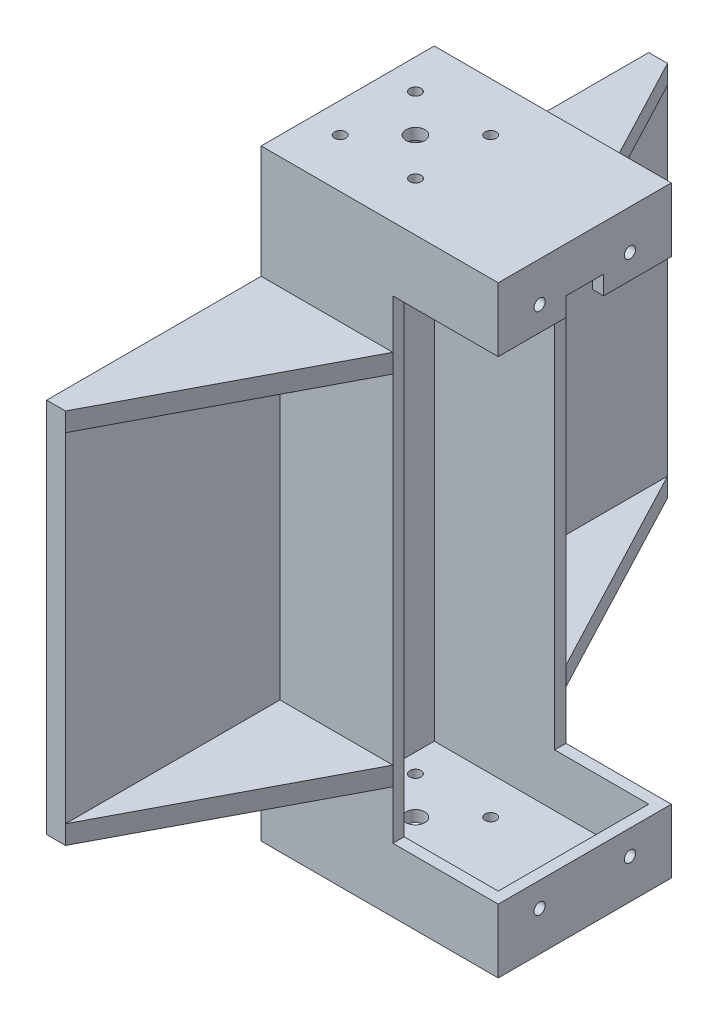
SolidWorks part; units mm, degrees
ref_plane "前视基准面" through (0, 0, 0) normal (0, 0, 1) x (1, 0, 0)
ref_plane "上视基准面" through (0, 0, 0) normal (0, 1, 0) x (1, 0, 0)
ref_plane "右视基准面" through (0, 0, 0) normal (1, 0, 0) x (0, 0, -1)
sketch "Sketch1" plane through (0, 0, 0) normal (0, 1, 0) x (1, 0, 0)
  line L1 (-30, 20) -> (30, 20)
  line L2 (-30, 20) -> (-30, -20)
  line L3 (-30, -20) -> (30, -20)
  line L4 (30, 20) -> (30, -20)
  line L5 (-30, 20) -> (30, -20) construction
  line L6 (-30, -20) -> (30, 20) construction
  point P0 (0, 0)
extrude "Extrude1" add sketch "Sketch1" along normal blind 3
sketch "Sketch2" plane through (0, 3, 0) normal (0, 1, 0) x (1, 0, 0)
  line L0 (-30, -20) -> (30, -20) construction
  line L1 (30, 20) -> (27, 20)
  line L2 (30, 20) -> (30, -20)
  line L3 (30, -20) -> (27, -20)
  line L4 (27, 20) -> (27, -20)
extrude "Extrude2" add sketch "Sketch2" along normal blind 14
sketch "Sketch4" plane through (27, 0, 0) normal (-1, 0, 0) x (0, 0, 1)
  circle A1 centre (-12, 10.5) radius 1.5
  circle A2 centre (12, 10.5) radius 1.5
extrude "Extrude3" cut sketch "Sketch4" against normal blind 15
sketch "Sketch5" plane through (0, 0, -20) normal (0, 0, -1) x (-1, 0, 0)
  line L1 (30, 3) -> (-27, 3)
  line L2 (-27, 3) -> (-27, 17)
  line L3 (-27, 17) -> (30, 17)
  line L4 (30, 17) -> (30, 3)
extrude "Extrude4" add sketch "Sketch5" against normal blind 3
sketch "Sketch6" plane through (0, 0, 20) normal (0, 0, 1) x (1, 0, 0)
  line L4 (27, 17) -> (-30, 17)
  line L5 (-30, 17) -> (-30, 3)
  line L6 (-30, 3) -> (27, 3)
  line L7 (27, 3) -> (27, 17)
  line L8 (27, 17) -> (-30, 17)
  line L9 (-30, 17) -> (-30, 3)
  line L10 (-30, 3) -> (27, 3)
  line L11 (27, 3) -> (27, 17)
  dimension "D1" = 0
extrude "Extrude5" add sketch "Sketch6" against normal blind 3
sketch "Sketch7" plane through (0, 3, 0) normal (0, 1, 0) x (1, 0, 0)
  circle A0 centre (-5, 10) radius 1.5
  circle A1 centre (-25, 10) radius 1.5
  circle A2 centre (-25, -10) radius 1.5
  circle A3 centre (-5, -10) radius 1.5
extrude "Extrude6" cut sketch "Sketch7" against normal blind 3
sketch "Sketch8" plane through (0, 3, 0) normal (0, 1, 0) x (1, 0, 0)
  circle A0 centre (-15, 0) radius 2.5
extrude "Extrude7" cut sketch "Sketch8" against normal blind 3
sketch "Sketch9" plane through (-30, 0, 0) normal (-1, 0, 0) x (0, 0, 1)
  line L1 (-20, 17) -> (20, 17)
  line L2 (-20, 17) -> (-20, 0)
  line L3 (-20, 0) -> (20, 0)
  line L4 (20, 17) -> (20, 0)
extrude "Extrude8" add sketch "Sketch9" along normal blind 3
sketch "Sketch10" plane through (0, 17, 0) normal (0, 1, 0) x (1, 0, 0)
  line L0 (-30, -17) -> (-30, 17) construction
  line L1 (-30, -17) -> (-30, 17)
  line L2 (-30, 17) -> (27, 17) construction
  line L3 (-30, 17) -> (2, 17)
  line L4 (-33, 20) -> (-33, -20)
  line L5 (-33, -20) -> (30, -20)
  line L6 (30, -20) -> (30, 20)
  line L7 (30, 20) -> (-33, 20)
  line L8 (-33, 20) -> (-33, -20)
  line L9 (-33, -20) -> (2, -20)
  line L11 (2, 20) -> (-33, 20)
  line L12 (27, -17) -> (-30, -17) construction
  line L13 (2, -17) -> (-30, -17)
  line L14 (2, 20) -> (2, 17)
  line L15 (2, -17) -> (2, -20)
  dimension "D1" = 0
extrude "Extrude9" add sketch "Sketch10" along normal blind 63
mirror "Mirror2" about plane through (0, 80, 0) normal (0, 1, 0) of bodies 114
sketch "Sketch11" plane through (0, 0, 20) normal (0, 0, 1) x (1, 0, 0)
  line L8 (-33, 0) -> (30, 0)
  line L9 (30, 0) -> (30, 17)
  line L10 (30, 17) -> (2, 17)
  line L11 (2, 17) -> (2, 143)
  line L12 (2, 143) -> (30, 143)
  line L13 (30, 143) -> (30, 160)
  line L14 (30, 160) -> (-33, 160)
  line L15 (-33, 160) -> (-33, 0)
  line L16 (-33, 0) -> (30, 0)
  line L17 (30, 0) -> (30, 17)
  line L18 (30, 17) -> (2, 17)
  line L19 (2, 17) -> (2, 143)
  line L20 (2, 143) -> (30, 143)
  line L21 (30, 143) -> (30, 160)
  line L22 (30, 160) -> (-33, 160)
  line L23 (-33, 160) -> (-33, 0)
  dimension "D1" = 0
extrude "Extrude10" add sketch "Sketch11" along normal blind 3
sketch "Sketch12" plane through (0, 0, -20) normal (0, 0, -1) x (-1, 0, 0)
  line L8 (-30, 0) -> (33, 0)
  line L9 (33, 0) -> (33, 160)
  line L10 (33, 160) -> (-30, 160)
  line L11 (-30, 160) -> (-30, 143)
  line L12 (-30, 143) -> (-2, 143)
  line L13 (-2, 143) -> (-2, 17)
  line L14 (-2, 17) -> (-30, 17)
  line L15 (-30, 17) -> (-30, 0)
  line L16 (-30, 0) -> (33, 0)
  line L17 (33, 0) -> (33, 160)
  line L18 (33, 160) -> (-30, 160)
  line L19 (-30, 160) -> (-30, 143)
  line L20 (-30, 143) -> (-2, 143)
  line L21 (-2, 143) -> (-2, 17)
  line L22 (-2, 17) -> (-30, 17)
  line L23 (-30, 17) -> (-30, 0)
  dimension "D1" = 0
extrude "Extrude11" add sketch "Sketch12" along normal blind 3
sketch "Sketch13" plane through (0, 0, 17) normal (0, 0, -1) x (-1, 0, 0)
  line L8 (-27, 17) -> (-27, 3)
  line L9 (-27, 3) -> (30, 3)
  line L10 (30, 3) -> (30, 157)
  line L11 (30, 157) -> (-27, 157)
  line L12 (-27, 157) -> (-27, 143)
  line L13 (-27, 143) -> (-2, 143)
  line L14 (-2, 143) -> (-2, 17)
  line L15 (-2, 17) -> (-27, 17)
  line L16 (-27, 17) -> (-27, 3)
  line L17 (-27, 3) -> (30, 3)
  line L18 (30, 3) -> (30, 157)
  line L19 (30, 157) -> (-27, 157)
  line L20 (-27, 157) -> (-27, 143)
  line L21 (-27, 143) -> (-2, 143)
  line L22 (-2, 143) -> (-2, 17)
  line L23 (-2, 17) -> (-27, 17)
  dimension "D1" = 0
extrude "Extrude12" cut sketch "Sketch13" against normal blind 3
sketch "Sketch14" plane through (0, 0, -17) normal (0, 0, 1) x (1, 0, 0)
  line L8 (27, 17) -> (2, 17)
  line L9 (2, 17) -> (2, 143)
  line L10 (2, 143) -> (27, 143)
  line L11 (27, 143) -> (27, 157)
  line L12 (27, 157) -> (-30, 157)
  line L13 (-30, 157) -> (-30, 3)
  line L14 (-30, 3) -> (27, 3)
  line L15 (27, 3) -> (27, 17)
  line L16 (27, 17) -> (2, 17)
  line L17 (2, 17) -> (2, 143)
  line L18 (2, 143) -> (27, 143)
  line L19 (27, 143) -> (27, 157)
  line L20 (27, 157) -> (-30, 157)
  line L21 (-30, 157) -> (-30, 3)
  line L22 (-30, 3) -> (27, 3)
  line L23 (27, 3) -> (27, 17)
  dimension "D1" = 0
extrude "Extrude13" cut sketch "Sketch14" against normal blind 3
sketch "Sketch15" plane through (-33, 0, 0) normal (-1, 0, 0) x (0, 0, 1)
  line L4 (80, 130) -> (-80, 130)
  line L5 (80, 130) -> (80, 30)
  line L6 (80, 30) -> (-80, 30)
  line L7 (-80, 130) -> (-80, 30)
  line L8 (80, 130) -> (-80, 30) construction
  line L9 (80, 30) -> (-80, 130) construction
  point P0 (0, 0)
  point P6 (0, 80)
extrude "Extrude14" add sketch "Sketch15" against normal blind 5
sketch "Sketch16" plane through (0, 30, 0) normal (0, -1, 0) x (1, 0, 0)
  line L0 (-28, -23) -> (2, -23)
  line L1 (-28, -23) -> (-28, -80)
  line L2 (-28, -80) -> (-28, -23) construction
  line L3 (2, -23) -> (-28, -80)
  line L4 (-28, 23) -> (2, 23)
  line L5 (-28, 23) -> (-28, 80)
  line L6 (-28, 23) -> (-28, 80) construction
  line L7 (2, 23) -> (-28, 80)
extrude "Extrude15" add sketch "Sketch16" against normal blind 5
sketch "Sketch17" plane through (0, 130, 0) normal (0, 1, 0) x (1, 0, 0)
  line L3 (-28, 80) -> (-28, 23)
  line L4 (-28, 23) -> (2, 23)
  line L5 (2, 23) -> (-28, 80)
  line L6 (-28, 80) -> (-28, 23)
  line L7 (-28, 23) -> (2, 23)
  line L8 (2, 23) -> (-28, 80)
  line L9 (-28, -23) -> (-28, -80)
  line L10 (-28, -80) -> (2, -23)
  line L11 (2, -23) -> (-28, -23)
  line L12 (-28, -23) -> (-28, -80)
  line L13 (-28, -80) -> (2, -23)
  line L14 (2, -23) -> (-28, -23)
  dimension "D1" = 0
  dimension "D2" = 0
extrude "Extrude16" add sketch "Sketch17" against normal blind 5
sketch "Sketch18" plane through (-28, 0, 0) normal (1, 0, 0) x (0, 0, -1)
  line L4 (20, 130) -> (-20, 130)
  line L5 (-20, 130) -> (-20, 30)
  line L6 (-20, 30) -> (20, 30)
  line L7 (20, 30) -> (20, 130)
  line L8 (20, 130) -> (-20, 130)
  line L9 (-20, 130) -> (-20, 30)
  line L10 (-20, 30) -> (20, 30)
  line L11 (20, 30) -> (20, 130)
  dimension "D1" = 0
extrude "Extrude17" cut sketch "Sketch18" against normal up to surface (2 mm away) up to face at (-30, 16.5, 0)
sketch "Sketch19" plane through (30, 0, 0) normal (1, 0, 0) x (0, 0, -1)
  line L0 (-23, 143) -> (23, 143) construction
  line L1 (5, 138) -> (-5, 138)
  line L2 (5, 138) -> (5, 148)
  line L3 (5, 148) -> (-5, 148)
  line L4 (-5, 138) -> (-5, 148)
  line L5 (5, 138) -> (-5, 148) construction
  line L6 (5, 148) -> (-5, 138) construction
  point P0 (0, 143)
extrude "Extrude18" cut sketch "Sketch19" against normal blind 5
